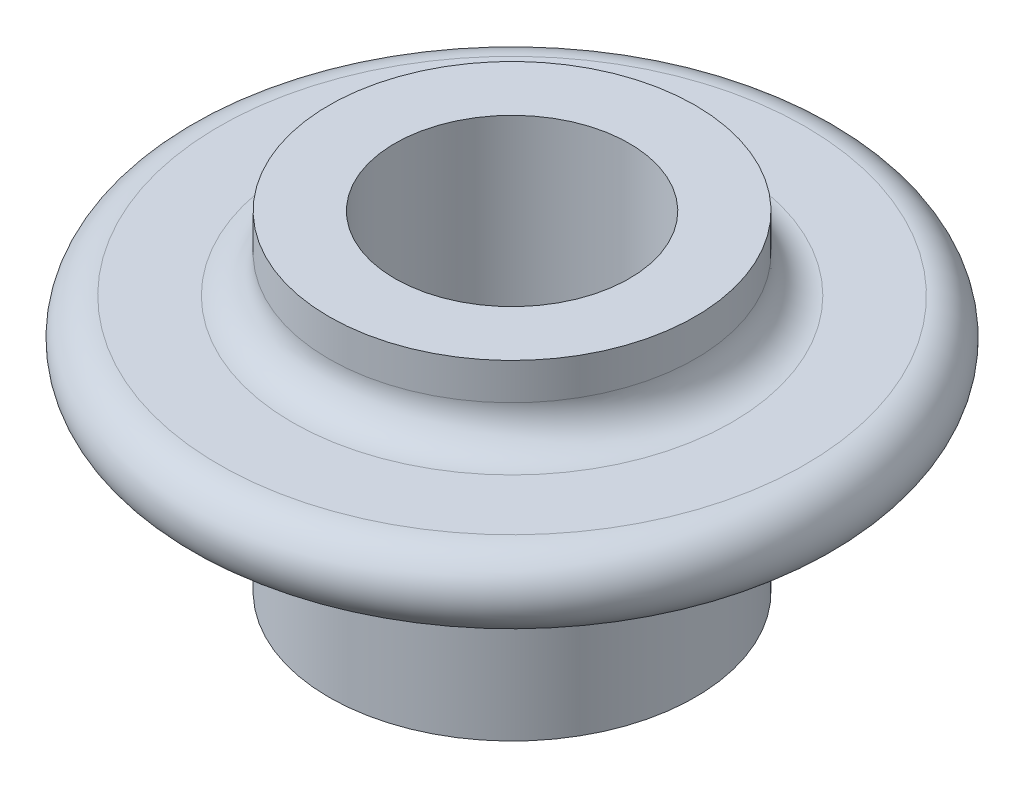
SolidWorks part; units mm, degrees
ref_plane "Front Plane" through (0, 0, 0) normal (0, 0, 1) x (1, 0, 0)
ref_plane "Top Plane" through (0, 0, 0) normal (0, 1, 0) x (1, 0, 0)
ref_plane "Right Plane" through (0, 0, 0) normal (1, 0, 0) x (0, 0, -1)
sketch "Sketch1" plane through (0, 0, 0) normal (0, 0, 1) x (1, 0, 0)
  line L0 (0, 0) -> (0, 45)
  line L1 (0, 45) -> (25, 45)
  line L2 (25, 45) -> (25, 35)
  line L3 (25, 35) -> (40, 35)
  line L4 (40, 25) -> (25, 25)
  line L5 (25, 25) -> (25, 0)
  line L6 (25, 0) -> (0, 0)
  arc A0 (40, 35) -> (40, 25) centre (40, 30) cw
  point P8 (45, 30)
  point P11 (12.5, 0)
  dimension "D1" = 25
  dimension "D2" = 10
  dimension "D3" = 10
  dimension "D4" = 45
  dimension "D5" = 45
revolve "Revolve1" add sketch "Sketch1" angle 360 about L0
hole_wizard "M36 Tapped Hole1" positions "3DSketch1" profile "Sketch2" tap size "M36" standard "ISO" end condition through all
sketch3d "3DSketch1"
  line L0 (0, 45, 0) -> (0, 35, 0) construction
  point P0 (0, 45, 0)
sketch "Sketch2" plane through (0, 45, 0) normal (1, 0, 0) x (0, 0, 1)
  line L0 (0, 0) -> (0, 45)
  line L1 (0, 45) -> (16, 45)
  line L2 (16, 45) -> (16, 0)
  line L5 (16, 0) -> (0, 0)
  line L11 (0, -6.35) -> (0, 107.95) construction
  dimension "Thru Tap Drill Dia." = 32
  dimension "Thru Tap Drill Depth" = 45
cosmetic thread "Hole Thread1" parameters "D2"=36
fillet "Fillet1" radius 5 1 edges at (0, 35, -25)
fillet "Fillet2" radius 1 1 edges at (0, 25, -25)
